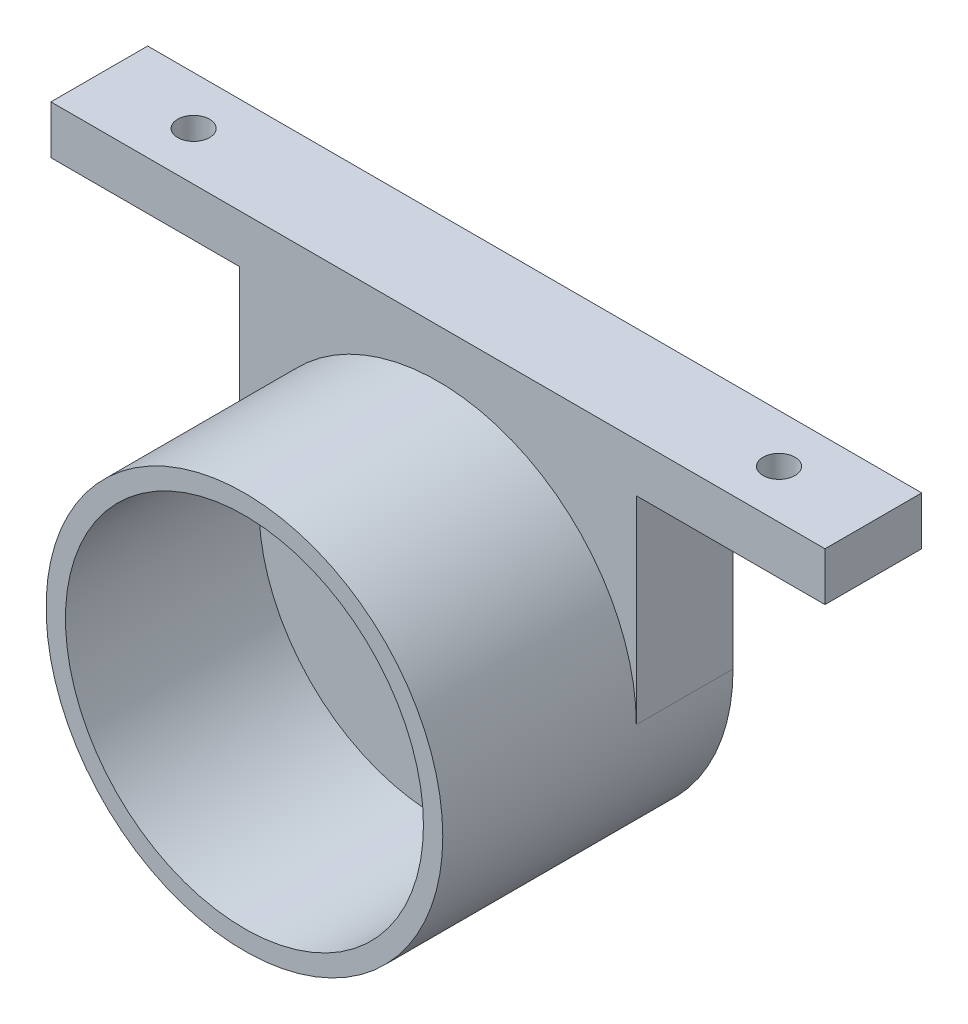
SolidWorks part; units mm, degrees
ref_plane "Plan de face" through (0, 0, 0) normal (0, 0, 1) x (1, 0, 0)
ref_plane "Plan de dessus" through (0, 0, 0) normal (0, 1, 0) x (1, 0, 0)
ref_plane "Plan de droite" through (0, 0, 0) normal (1, 0, 0) x (0, 0, -1)
sketch "Esquisse1" plane through (0, 0, 0) normal (0, 0, 1) x (1, 0, 0)
  circle A0 centre (0, 0) radius 18.5
  circle A1 centre (0, 0) radius 20.5
  dimension "D1" = 37
  dimension "D2" = 41
extrude "Boss.-Extru.1" add sketch "Esquisse1" along normal blind 20
sketch "Esquisse2" plane through (0, 0, 0) normal (0, 0, -1) x (-1, 0, 0)
  circle A0 centre (0, 0) radius 20.5
  dimension "D1" = 41
extrude "Boss.-Extru.2" add sketch "Esquisse2" along normal blind 10
ref_plane "Plan1" through (0, 20.5, 0) normal (0, 1, 0) x (1, 0, 0)
sketch "Esquisse5" plane through (0, 20.5, 0) normal (0, 1, 0) x (1, 0, 0)
  line L1 (0, 0) -> (40, 0)
  line L3 (10, 10) -> (40, 10)
  line L4 (40, 0) -> (40, 10)
  line L5 (0, 0) -> (-40, 0)
  line L7 (10, 10) -> (-40, 10)
  line L8 (-40, 0) -> (-40, 10)
  dimension "D1" = 10
  dimension "D2" = 40
  dimension "D3" = 40
extrude "Boss.-Extru.4" add sketch "Esquisse5" along normal blind 5 separate body
ref_plane "Plan3" through (0, 0, -10) normal (0, 0, 1) x (1, 0, 0)
sketch "Esquisse7" plane through (0, 0, -10) normal (0, 0, 1) x (1, 0, 0)
  line L0 (20.5, 20.5) -> (20.5, 0)
  line L1 (16.5, 20.5) -> (-16.5, 20.5) construction
  line L2 (-20.5, 20.5) -> (-20.5, 0)
  line L3 (40, 20.5) -> (-40, 20.5) construction
  line L4 (20.5, 20.5) -> (0, 20.5)
  line L5 (0, 20.5) -> (-20.5, 20.5)
  circle A0 centre (0, 0) radius 20.5 construction
  arc A1 (20.5, 0) -> (0, 20.5) centre (0, 0) ccw
  arc A2 (-20.5, 0) -> (0, 20.5) centre (0, 0) cw
  dimension "D1" = 20.5
  dimension "D2" = 20.5
  dimension "D3" = 20.5
  dimension "D4" = 20.5
extrude "Boss.-Extru.5" add sketch "Esquisse7" along normal blind 10 contours A1 L0 L4 | L2 A2 L5
hole_wizard "Trou taraudé M41" positions "Esquisse11" profile "Esquisse12" tap size "M4" standard "ISO" end condition up to next
sketch "Esquisse11" plane through (0, 20.5, 0) normal (0, -1, 0) x (-1, 0, 0)
  line L0 (-40, 0) -> (-40, 10) construction
  line L1 (40, 10) -> (40, 0) construction
  point P0 (-30.25, 5)
  point P2 (30.25, 5)
  point P13 (40, 0)
  dimension "D1" = 9.75
  dimension "D2" = 9.75
  dimension "D3" = 5
  dimension "D4" = 5
sketch "Esquisse12" plane through (30.25, 20.5, -5) normal (1, 0, 0) x (0, 0, -1)
  line L0 (0, 0) -> (0, 5)
  line L1 (0, 5) -> (1.65, 5)
  line L2 (1.65, 5) -> (1.65, 0.375)
  line L3 (1.65, 0.375) -> (2.025, 0)
  line L5 (2.025, 0) -> (0, 0)
  line L6 (-1.65, 0.375) -> (-2.025, 0) construction
  line L11 (0, -6.35) -> (0, 107.95) construction
  dimension "Diamètre du trou pour taraudage jusqu'au prochain" = 3.3
  dimension "Profondeur du trou pour taraudage jusqu'au prochain" = 5
  dimension "Diamètre du fraisage entrant" = 4.05
  dimension "Angle du fraisage entrant" = 90
cosmetic thread "Filetage de perçage1" parameters "D2"=4
cosmetic thread "Filetage de perçage2" parameters "D2"=4
